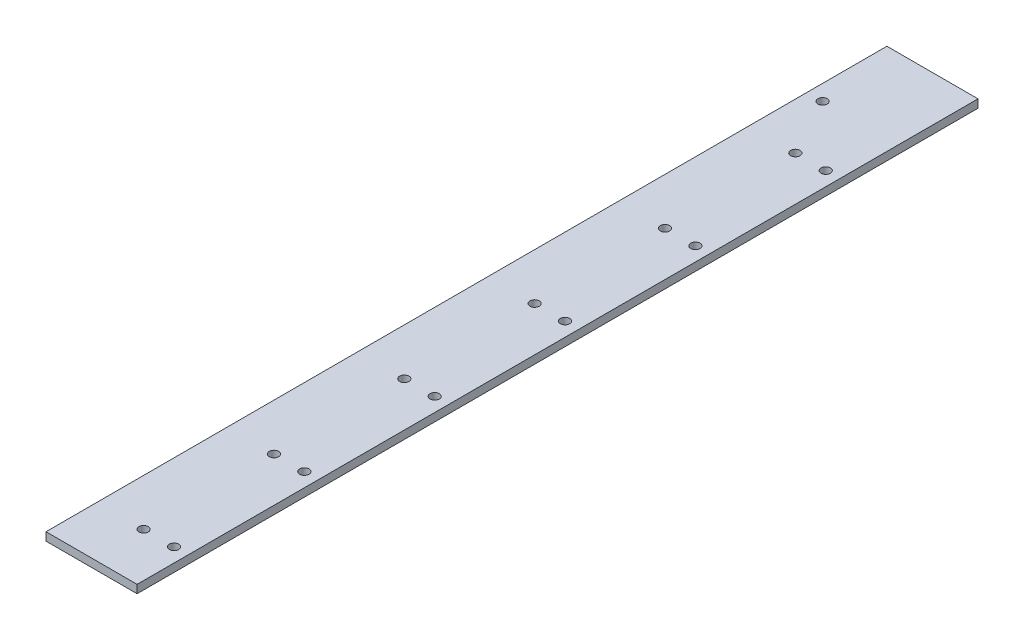
SolidWorks part; units mm, degrees
ref_plane "Front Plane" through (0, 0, 0) normal (0, 0, 1) x (1, 0, 0)
ref_plane "Top Plane" through (0, 0, 0) normal (0, 1, 0) x (1, 0, 0)
ref_plane "Right Plane" through (0, 0, 0) normal (1, 0, 0) x (0, 0, -1)
sketch "Sketch1" plane through (0, 0, 0) normal (0, 0, 1) x (1, 0, 0)
  line L1 (-19.5, -1.75) -> (19.5, -1.75)
  line L2 (-19.5, -1.75) -> (-19.5, 1.75)
  line L3 (-19.5, 1.75) -> (19.5, 1.75)
  line L4 (19.5, -1.75) -> (19.5, 1.75)
  line L5 (-19.5, -1.75) -> (19.5, 1.75) construction
  line L6 (-19.5, 1.75) -> (19.5, -1.75) construction
  point P0 (0, 0)
  dimension "D1" = 39
  dimension "D2" = 3.5
extrude "Boss-Extrude1" add sketch "Sketch1" along normal blind 360 contours L3 L4 L1 L2
sketch "Sketch2" plane through (0, 1.75, 0) normal (0, 1, 0) x (1, 0, 0)
  line L1 (-19.5, 0) -> (19.5, 0) construction
  line L2 (-19.5, -360) -> (-19.5, 0) construction
  circle A0 centre (-12.8207, -34.2249) radius 2
  dimension "D3" = 4
  dimension "D1" = 34.2249
  dimension "D2" = 6.6793
extrude "Cut-Extrude1" cut sketch "Sketch2" against normal blind 10
sketch "Sketch3" plane through (0, 1.75, 0) normal (0, 1, 0) x (1, 0, 0)
  line L0 (-19.5, 0) -> (19.5, 0) construction
  line L1 (-19.5, -360) -> (-19.5, 0) construction
  circle A0 centre (0.5, -59.2) radius 2
  circle A1 centre (13.5, -59.2) radius 2
  point P4 (0, 0)
  dimension "D4" = 4
  dimension "D1" = 59.2
  dimension "D2" = 13
  dimension "D3" = 20
extrude "Cut-Extrude2" cut sketch "Sketch3" against normal blind 10 contours A0 | A1
pattern_linear "LPattern1" count 6 spacing 55.8 along (0, 0, 1) of "Cut-Extrude2"
